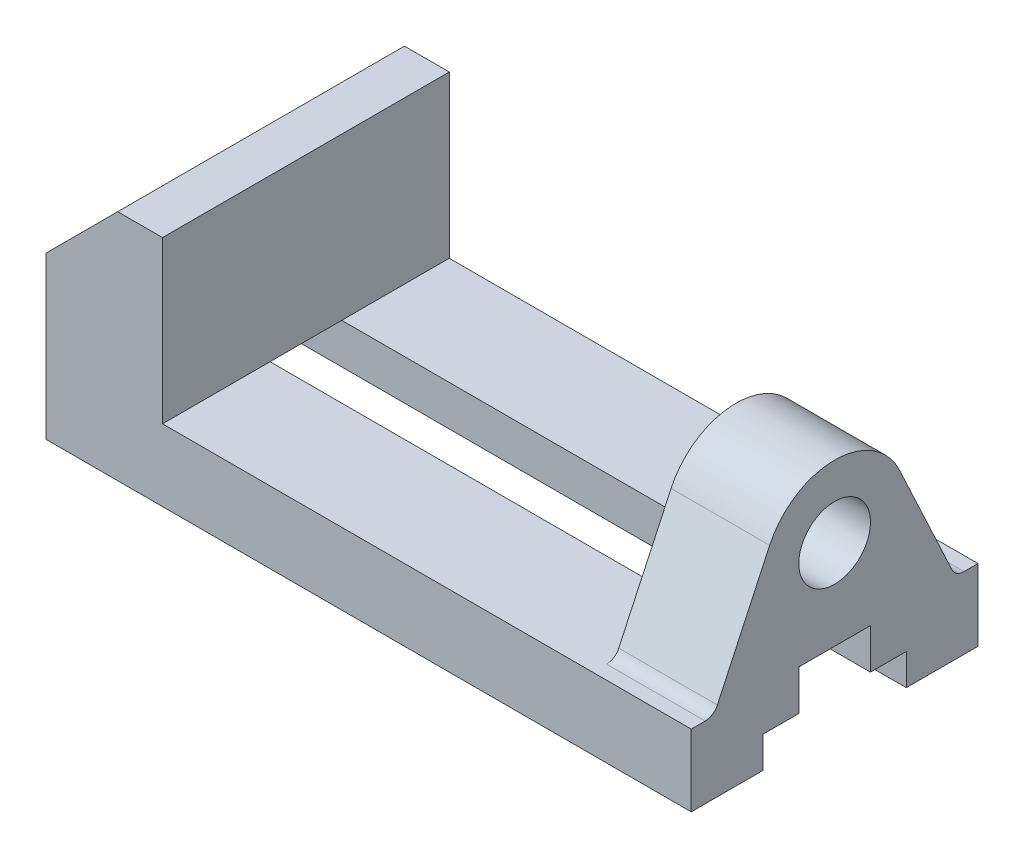
SolidWorks part; units mm, degrees
ref_plane "Front Plane" through (0, 0, 0) normal (0, 0, 1) x (1, 0, 0)
ref_plane "Top Plane" through (0, 0, 0) normal (0, 1, 0) x (1, 0, 0)
ref_plane "Right Plane" through (0, 0, 0) normal (1, 0, 0) x (0, 0, -1)
sketch "Sketch1" plane through (0, 0, 0) normal (0, 1, 0) x (1, 0, 0)
  line L1 (-72, -32) -> (72, -32)
  line L2 (-72, -32) -> (-72, 32)
  line L3 (-72, 32) -> (72, 32)
  line L4 (72, -32) -> (72, 32)
  line L5 (-72, -32) -> (72, 32) construction
  line L6 (-72, 32) -> (72, -32) construction
  point P0 (0, 0)
  dimension "D1" = 64
  dimension "D2" = 144
extrude "Boss-Extrude1" add sketch "Sketch1" along normal blind 16
sketch "Sketch2" plane through (0, 0, 32) normal (0, 0, 1) x (1, 0, 0)
  line L0 (-46, 16) -> (-46, 52)
  line L1 (-72, 16) -> (72, 16) construction
  line L2 (-46, 52) -> (-56, 52)
  line L4 (-72, 16) -> (-46, 16)
  line L5 (-56, 52) -> (-72, 36)
  line L6 (-72, 36) -> (-72, 16)
  dimension "D1" = 16
  dimension "D2" = 16
  dimension "D3" = 10
  dimension "D4" = 36
extrude "Boss-Extrude2" add sketch "Sketch2" against normal up to surface (64 mm away) up to face at (0, 8, -32)
sketch "Sketch3" plane through (72, 0, 0) normal (1, 0, 0) x (0, 0, -1)
  line L0 (-32, 0) -> (32, 0) construction
  line L1 (-14.5009, 42.7619) -> (-26.9802, 16)
  line L2 (0, 36) -> (0, 0) construction
  line L3 (32, 16) -> (-32, 16) construction
  line L4 (14.5009, 42.7619) -> (26.9802, 16)
  line L5 (-26.9802, 16) -> (26.9802, 16)
  circle A0 centre (0, 36) radius 8
  arc A1 (14.5009, 42.7619) -> (-14.5009, 42.7619) centre (0, 36) ccw
  dimension "D1" = 16
  dimension "D2" = 36
  dimension "D3" = 32
  dimension "D4" = 50
extrude "Boss-Extrude3" add sketch "Sketch3" against normal blind 22
fillet "Fillet1" radius 3 2 edges at (61, 16, -26.9802) (61, 16, 26.9802)
sketch "Sketch4" plane through (72, 0, 0) normal (1, 0, 0) x (0, 0, -1)
  line L0 (-16, 0) -> (-16, 7)
  line L1 (-32, 0) -> (32, 0) construction
  line L2 (-16, 7) -> (-8, 7)
  line L3 (-8, 7) -> (-8, 16)
  line L4 (-8, 16) -> (8, 16)
  line L5 (0, 0) -> (0, 16) construction
  line L6 (-32, 16) -> (-28.8914, 16) construction
  line L7 (16, 0) -> (16, 7)
  line L8 (16, 7) -> (8, 7)
  line L9 (8, 7) -> (8, 16)
  line L10 (-16, 0) -> (16, 0)
  dimension "D1" = 7
  dimension "D2" = 32
  dimension "D3" = 16
extrude "Cut-Extrude1" cut sketch "Sketch4" against normal through all
hole_wizard "M6x1.0 Tapped Hole1" positions "Sketch5" profile "Sketch6" tap size "M6x1.0" standard "ANSI Metric"
sketch "Sketch5" plane through (0, 0, 0) normal (0, -1, 0) x (-1, 0, 0)
  line L1 (-72, -32) -> (-72, -16) construction
  line L2 (0, 0) -> (36, 0) construction
  point P0 (-34, -22)
  point P2 (36, -22)
  point P4 (36, 22)
  point P6 (-34, 22)
  dimension "D1" = 38
  dimension "D2" = 70
  dimension "D3" = 44
sketch "Sketch6" plane through (34, 0, 22) normal (1, 0, 0) x (0, 0, -1)
  line L0 (0, 0) -> (0, 11.4434)
  line L1 (0, 11.4434) -> (2.5, 10)
  line L2 (2.5, 10) -> (2.5, 0)
  line L5 (2.5, 0) -> (0, 0)
  line L10 (0, 11.4434) -> (-2.5, 10) construction
  line L11 (0, -6.35) -> (0, 107.95) construction
  dimension "Tap Drill Dia." = 5
  dimension "Tap Drill Depth" = 10
  dimension "Drill Angle" = 120
cosmetic thread "Hole Thread1" parameters "D1"=12, "D2"=6
cosmetic thread "Hole Thread2" parameters "D1"=12, "D2"=6
cosmetic thread "Hole Thread3" parameters "D1"=12, "D2"=6
cosmetic thread "Hole Thread4" parameters "D1"=12, "D2"=6
